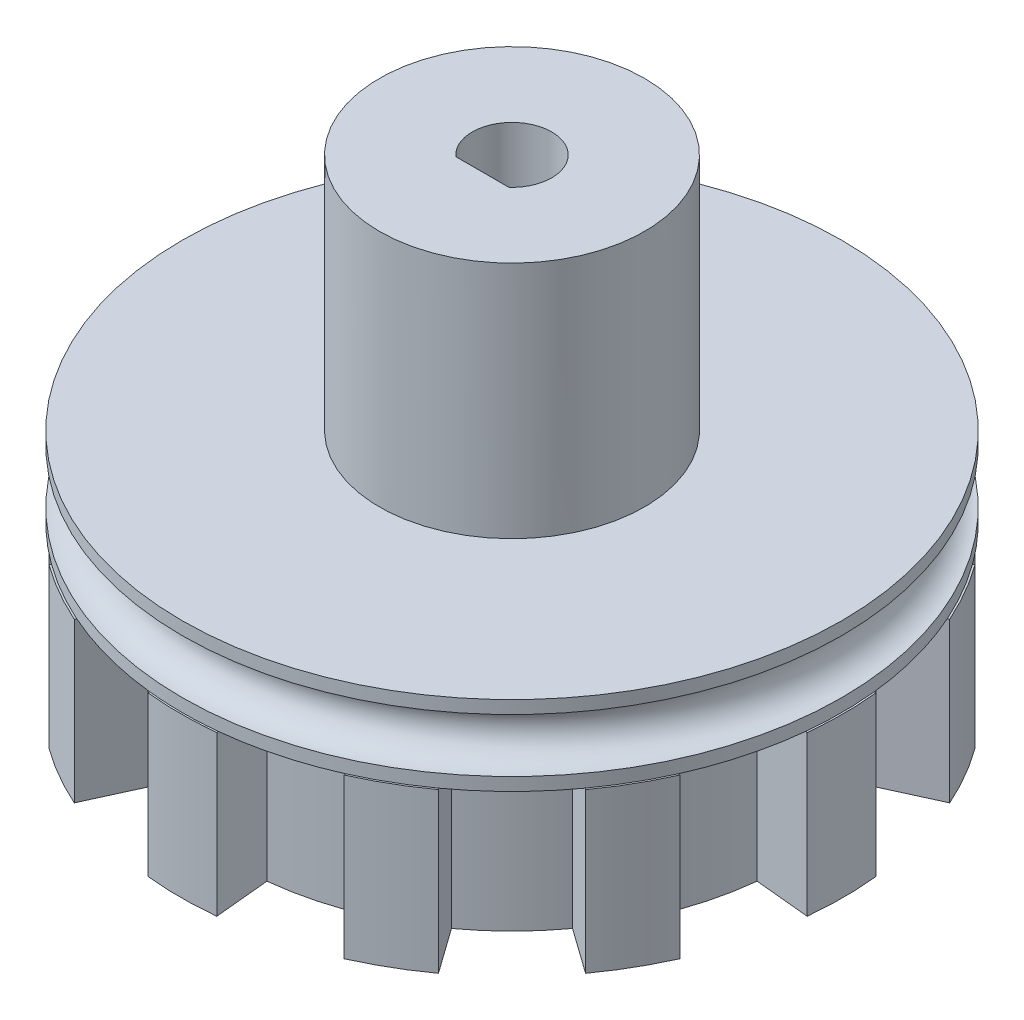
SolidWorks part; units mm, degrees
ref_plane "前视基准面" through (0, 0, 0) normal (0, 0, 1) x (1, 0, 0)
ref_plane "上视基准面" through (0, 0, 0) normal (0, 1, 0) x (1, 0, 0)
ref_plane "右视基准面" through (0, 0, 0) normal (1, 0, 0) x (0, 0, -1)
sketch "草图2" plane through (0, 0, 0) normal (0, 1, 0) x (1, 0, 0)
  line L0 (0, 13.0353) -> (0, -8.9877) construction
  line L1 (-1.1, 10.3417) -> (-1.3, 12.4322)
  line L2 (1.1, 10.3417) -> (1.3, 12.4322)
  line L3 (4.2182, 9.5061) -> (5.0903, 11.4166)
  line L4 (6.1235, 8.4061) -> (7.3419, 10.1166)
  line L5 (8.4061, 6.1235) -> (10.1166, 7.3419)
  line L6 (9.5061, 4.2182) -> (11.4166, 5.0903)
  line L7 (10.3417, 1.1) -> (12.4322, 1.3)
  line L8 (10.3417, -1.1) -> (12.4322, -1.3)
  line L9 (9.5061, -4.2182) -> (11.4166, -5.0903)
  line L10 (8.4061, -6.1235) -> (10.1166, -7.3419)
  line L11 (6.1235, -8.4061) -> (7.3419, -10.1166)
  line L12 (4.2182, -9.5061) -> (5.0903, -11.4166)
  line L13 (1.1, -10.3417) -> (1.3, -12.4322)
  line L14 (-1.1, -10.3417) -> (-1.3, -12.4322)
  line L15 (-4.2182, -9.5061) -> (-5.0903, -11.4166)
  line L16 (-6.1235, -8.4061) -> (-7.3419, -10.1166)
  line L17 (-8.4061, -6.1235) -> (-10.1166, -7.3419)
  line L18 (-9.5061, -4.2182) -> (-11.4166, -5.0903)
  line L19 (-10.3417, -1.1) -> (-12.4322, -1.3)
  line L20 (-10.3417, 1.1) -> (-12.4322, 1.3)
  line L21 (-9.5061, 4.2182) -> (-11.4166, 5.0903)
  line L22 (-8.4061, 6.1235) -> (-10.1166, 7.3419)
  line L23 (-6.1235, 8.4061) -> (-7.3419, 10.1166)
  line L24 (-4.2182, 9.5061) -> (-5.0903, 11.4166)
  arc A0 (-1.1, 10.3417) -> (-4.2182, 9.5061) centre (0, 0) ccw
  arc A1 (1.3, 12.4322) -> (-1.3, 12.4322) centre (0, 0) ccw
  arc A2 (7.3419, 10.1166) -> (5.0903, 11.4166) centre (0, 0) ccw
  arc A3 (11.4166, 5.0903) -> (10.1166, 7.3419) centre (0, 0) ccw
  arc A4 (12.4322, -1.3) -> (12.4322, 1.3) centre (0, 0) ccw
  arc A5 (10.1166, -7.3419) -> (11.4166, -5.0903) centre (0, 0) ccw
  arc A6 (5.0903, -11.4166) -> (7.3419, -10.1166) centre (0, 0) ccw
  arc A7 (-1.3, -12.4322) -> (1.3, -12.4322) centre (0, 0) ccw
  arc A8 (-7.3419, -10.1166) -> (-5.0903, -11.4166) centre (0, 0) ccw
  arc A9 (-11.4166, -5.0903) -> (-10.1166, -7.3419) centre (0, 0) ccw
  arc A10 (-12.4322, 1.3) -> (-12.4322, -1.3) centre (0, 0) ccw
  arc A11 (-10.1166, 7.3419) -> (-11.4166, 5.0903) centre (0, 0) ccw
  arc A12 (-5.0903, 11.4166) -> (-7.3419, 10.1166) centre (0, 0) ccw
  arc A13 (-6.1235, 8.4061) -> (-8.4061, 6.1235) centre (0, 0) ccw
  arc A14 (-9.5061, 4.2182) -> (-10.3417, 1.1) centre (0, 0) ccw
  arc A15 (-10.3417, -1.1) -> (-9.5061, -4.2182) centre (0, 0) ccw
  arc A16 (-8.4061, -6.1235) -> (-6.1235, -8.4061) centre (0, 0) ccw
  arc A17 (-4.2182, -9.5061) -> (-1.1, -10.3417) centre (0, 0) ccw
  arc A18 (1.1, -10.3417) -> (4.2182, -9.5061) centre (0, 0) ccw
  arc A19 (6.1235, -8.4061) -> (8.4061, -6.1235) centre (0, 0) ccw
  arc A20 (9.5061, -4.2182) -> (10.3417, -1.1) centre (0, 0) ccw
  arc A21 (10.3417, 1.1) -> (9.5061, 4.2182) centre (0, 0) ccw
  arc A22 (8.4061, 6.1235) -> (6.1235, 8.4061) centre (0, 0) ccw
  arc A23 (4.2182, 9.5061) -> (1.1, 10.3417) centre (0, 0) ccw
  point P1 (0, 0)
  point P3 (0, 0)
  point P6 (-1.0568, 9.8899)
  point P7 (0, 0)
  point P56 (0, 0)
  point P57 (0, 0)
  dimension "D1" = 20.8
  dimension "D2" = 25
  dimension "D3" = 1.1
  dimension "D5" = 2.6
  dimension "D6" = 1.3
  dimension "D7" = 1.1
  dimension "D4" = 12
extrude "凸台-拉伸1" add sketch "草图2" along normal blind 6
sketch "草图3" plane through (0, 6, 0) normal (0, 1, 0) x (1, 0, 0)
  circle A0 centre (0, 0) radius 1.4
extrude "切除-拉伸1" cut sketch "草图3" against normal blind 6
sketch "草图4" plane through (0, 6, 0) normal (0, 1, 0) x (1, 0, 0)
  circle A0 centre (0, 0) radius 5
extrude "凸台-拉伸2" add sketch "草图4" along normal blind 12
sketch "草图5" plane through (0, 18, 0) normal (0, 1, 0) x (1, 0, 0)
  line L0 (-1, -1.118) -> (1, -1.118)
  arc A0 (1, -1.118) -> (-1, -1.118) centre (0, 0) ccw
  dimension "D1" = 3
  dimension "D2" = 2
extrude "切除-拉伸2" cut sketch "草图5" against normal blind 12
sketch "草图7" plane through (0, 0, 0) normal (1, 0, 0) x (0, 0, -1)
  line L0 (5, 6) -> (5, 18) construction
  line L1 (5, 9) -> (12.4322, 9)
  line L2 (5, 9) -> (5, 6)
  line L3 (5, 6) -> (12.4322, 6)
  line L4 (12.4322, 9) -> (12.4322, 8.5119)
  line L5 (12.4322, 6.4881) -> (12.4322, 6)
  line L6 (0, 19.9198) -> (0, -5.1703) construction
  arc A0 (12.4322, 8.5119) -> (12.4322, 6.4881) centre (12.4029, 7.5) ccw
  dimension "D1" = 3
revolve "旋转1" add sketch "草图7" angle 360 about L6
